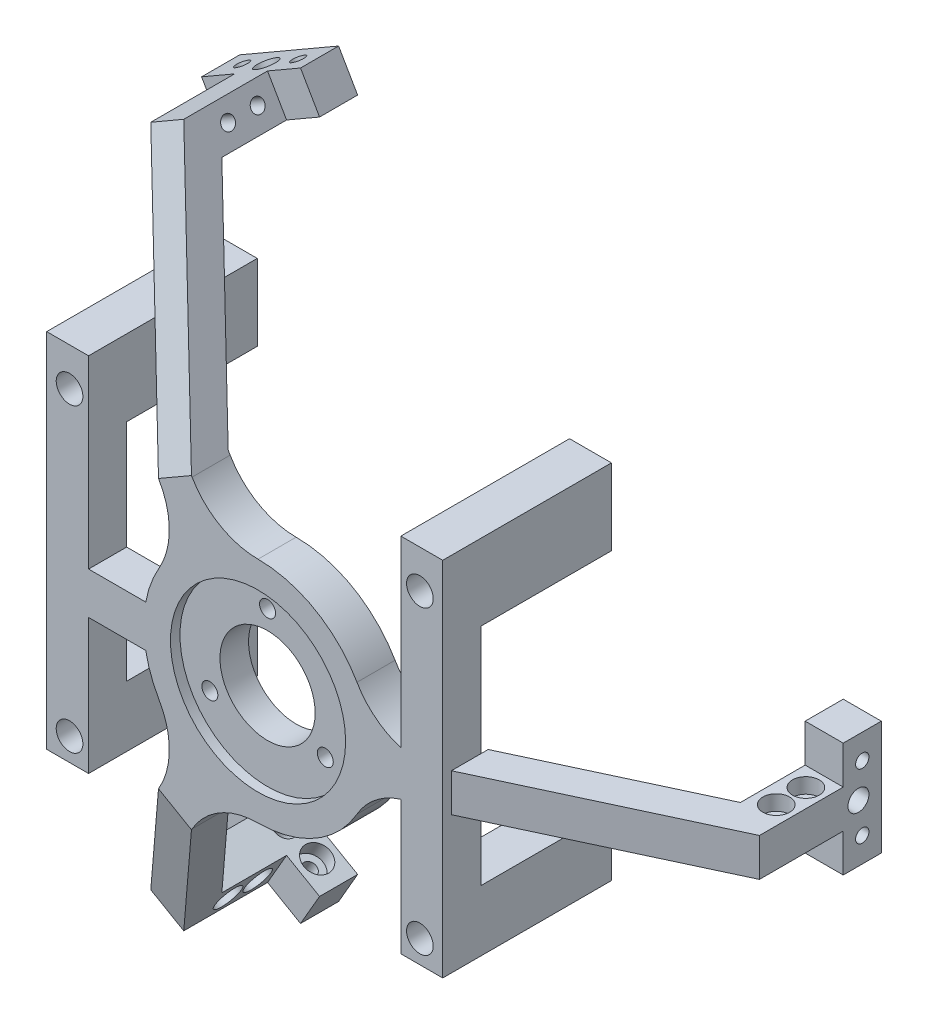
SolidWorks part; units mm, degrees
ref_plane "Plan de face" through (0, 0, 0) normal (0, 0, 1) x (1, 0, 0)
ref_plane "Plan de dessus" through (0, 0, 0) normal (0, 1, 0) x (1, 0, 0)
ref_plane "Plan de droite" through (0, 0, 0) normal (1, 0, 0) x (0, 0, -1)
sketch "Esquisse1" plane through (0, 0, 0) normal (0, 0, 1) x (1, 0, 0)
  line L0 (0, 0) -> (93.67, 0) construction
  line L1 (93.67, 15) -> (103.67, 15)
  line L2 (93.67, 15) -> (93.67, -15)
  line L3 (93.67, -15) -> (103.67, -15)
  line L4 (103.67, 15) -> (103.67, -15)
  line L5 (-33.8446, -88.6206) -> (-59.8254, -73.6206)
  line L6 (-33.8446, -88.6206) -> (-38.8446, -97.2809)
  line L7 (-38.8446, -97.2809) -> (-64.8254, -82.2809)
  line L8 (-59.8254, -73.6206) -> (-64.8254, -82.2809)
  line L9 (-59.8254, 73.6206) -> (-33.8446, 88.6206)
  line L10 (-59.8254, 73.6206) -> (-64.8254, 82.2809)
  line L11 (-64.8254, 82.2809) -> (-38.8446, 97.2809)
  line L12 (-33.8446, 88.6206) -> (-38.8446, 97.2809)
  point P17 (0, 0)
  dimension "D1" = 30
  dimension "D2" = 10
  dimension "D3" = 93.67
  dimension "D4" = 3
extrude "Boss.-Extru.1" add sketch "Esquisse1" along normal blind 10
sketch "Esquisse2" plane through (0, 0, 10) normal (0, 0, 1) x (1, 0, 0)
  line L0 (-57.0272, 86.7831) -> (-46.3532, 92.9458)
  line L1 (-38.8446, 97.2809) -> (-64.8254, 82.2809) construction
  line L2 (93.67, 15) -> (93.67, -15) construction
  line L3 (93.67, 5) -> (103.67, 5)
  line L4 (93.67, 5) -> (93.67, -5)
  line L5 (93.67, -5) -> (103.67, -5)
  line L6 (103.67, 5) -> (103.67, -5)
  line L7 (103.67, -15) -> (103.67, 15) construction
  line L8 (-42.5049, -83.6206) -> (-51.1651, -78.6206)
  line L9 (-42.5049, -83.6206) -> (-47.5049, -92.2809)
  line L10 (-47.5049, -92.2809) -> (-56.1651, -87.2809)
  line L11 (-51.1651, -78.6206) -> (-56.1651, -87.2809)
  line L12 (-51.1651, 78.6206) -> (-42.5049, 83.6206)
  line L13 (-51.1651, 78.6206) -> (-56.1651, 87.2809)
  line L14 (-56.1651, 87.2809) -> (-47.5049, 92.2809)
  line L15 (-42.5049, 83.6206) -> (-47.5049, 92.2809)
  point P12 (93.67, 0)
  point P13 (93.67, 0)
  point P24 (0, 0)
  line M6 (-59.8254, 73.6206) -> (-33.8446, 88.6206)
  dimension "D1" = 3
extrude "Boss.-Extru.2" add sketch "Esquisse2" along normal blind 40 contours L15 L0 L13 M6 | L6 L3 L4 L5 | L8 L11 L10 L9
sketch "Esquisse3" plane through (0, 0, 50) normal (0, 0, 1) x (1, 0, 0)
  line L0 (103.67, 5) -> (103.67, -5) construction
  line L1 (-47.5049, -92.2809) -> (-56.1651, -87.2809) construction
  line L2 (-47.5049, 92.2809) -> (-56.1651, 87.2809) construction
  line L3 (103.67, 5) -> (103.67, -5)
  line L4 (-47.5049, -92.2809) -> (-56.1651, -87.2809)
  line L5 (-47.5049, 92.2809) -> (-56.1651, 87.2809)
  line L6 (-56.1651, -87.2809) -> (-19.1203, -23.1174)
  line L7 (-47.5049, -92.2809) -> (-10.4601, -28.1174)
  line L8 (103.67, -5) -> (29.5804, -5)
  line L9 (103.67, 5) -> (29.5804, 5)
  line L10 (-56.1651, 87.2809) -> (-19.1203, 23.1174)
  line L11 (-47.5049, 92.2809) -> (-10.4601, 28.1174)
  line L12 (-51.1651, -78.6206) -> (-56.1651, -87.2809) construction
  line L13 (-42.5049, -83.6206) -> (-47.5049, -92.2809) construction
  line L14 (93.67, -5) -> (103.67, -5) construction
  line L15 (93.67, 5) -> (103.67, 5) construction
  line L16 (-51.1651, 78.6206) -> (-56.1651, 87.2809) construction
  line L17 (-42.5049, 83.6206) -> (-47.5049, 92.2809) construction
  arc A0 (-19.1203, -23.1174) -> (-19.1203, 23.1174) centre (0, 0) cw
  arc A1 (-10.4601, 28.1174) -> (29.5804, 5) centre (0, 0) cw
  arc A2 (29.5804, -5) -> (-10.4601, -28.1174) centre (0, 0) cw
  dimension "D1" = 30
extrude "Boss.-Extru.3" add sketch "Esquisse3" along normal blind 10
chamfer "Chanfrein1" distance 23 angle 65 3 edges at (93.67, 0, 50) (-46.835, -81.1206, 50) (-46.835, 81.1206, 50)
chamfer "Chanfrein2" distance 28 angle 65 3 edges at (-51.835, -89.7809, 60) (-51.835, 89.7809, 60) (103.67, 0, 60)
fillet "Congé1" radius 20 6 edges at (29.5804, -5, 55) (-10.4601, -28.1174, 55) (-19.1203, -23.1174, 55) (-19.1203, 23.1174, 55) (29.5804, 5, 55) (-10.4601, 28.1174, 55)
sketch "Esquisse4" plane through (0, 0, 60) normal (0, 0, 1) x (1, 0, 0)
  circle A0 centre (0, 0) radius 12.5
  dimension "D1" = 25
extrude "Enlèv. mat.-Extru.1" cut sketch "Esquisse4" against normal up to next
sketch "Esquisse5" plane through (0, 0, 60) normal (0, 0, 1) x (1, 0, 0)
  circle A0 centre (0, 0) radius 23
  dimension "D1" = 46
extrude "Enlèv. mat.-Extru.2" cut sketch "Esquisse5" against normal blind 2.5
sketch "Esquisse6" plane through (0, 0, 57.5) normal (0, 0, 1) x (1, 0, 0)
  line L0 (0, 17.5) -> (0, 0) construction
  circle A0 centre (0, 17.5) radius 2.1
  circle A1 centre (15.1554, -8.75) radius 2.1
  circle A2 centre (-15.1554, -8.75) radius 2.1
  point P10 (0, 0)
  dimension "D2" = 4.2
  dimension "D1" = 17.5
  dimension "D3" = 3
extrude "Enlèv. mat.-Extru.3" cut sketch "Esquisse6" against normal up to next
sketch "Esquisse7" plane through (0, 0, 50) normal (0, 0, -1) x (-1, 0, 0)
  line L0 (0, 0) -> (44.5, 0) construction
  line L1 (-37.5, -41) -> (-48.5, -41)
  line L2 (-37.5, -41) -> (-37.5, 54)
  line L3 (-37.5, 54) -> (-48.5, 54)
  line L4 (-48.5, -41) -> (-48.5, 54)
  line L5 (55.5, -41) -> (44.5, -41)
  line L6 (44.5, -41) -> (44.5, -5.5)
  line L7 (44.5, -5.5) -> (29.4915, -5.5)
  line L8 (55.5, -41) -> (55.5, 54)
  line L9 (55.5, 54) -> (44.5, 54)
  line L10 (44.5, 54) -> (44.5, 5.5)
  line L11 (44.5, 5.5) -> (29.4915, 5.5)
  line L12 (44.5, -5.5) -> (44.5, 5.5) construction
  arc A0 (25.9808, -15) -> (25.9808, 15) centre (0, 0) ccw construction
  arc A1 (29.4915, -5.5) -> (29.4915, 5.5) centre (0, 0) ccw
  point P7 (-43, 54)
  point P22 (44.5, 0)
  point P28 (50, 54)
  dimension "D1" = 11
  dimension "D2" = 41
  dimension "D3" = 95
  dimension "D4" = 43
  dimension "D5" = 93
extrude "Boss.-Extru.4" add sketch "Esquisse7" along normal blind 34.3 and the other way up to surface other way up to face at (23, 0, 60)
sketch "Esquisse8" plane through (0, 0, 15.7) normal (0, 0, -1) x (-1, 0, 0)
  line L0 (-48.5, 6.5) -> (55.5, 6.5) construction
  line L1 (-48.5, 54) -> (-48.5, -41) construction
  line L2 (55.5, -41) -> (55.5, 54) construction
  line L3 (49.5, 44) -> (-42.5, 44) construction
  line L4 (3.5, 6.5) -> (3.5, 44) construction
  line L5 (-48.5, -41) -> (-37.5, -41) construction
  circle A0 centre (49.5, 44) radius 1.75
  circle A1 centre (-42.5, 44) radius 1.75
  circle A2 centre (-42.5, -35) radius 1.75
  circle A3 centre (49.5, -35) radius 1.75
  dimension "D4" = 3.5
  dimension "D1" = 92
  dimension "D2" = 79
  dimension "D3" = 6
extrude "Enlèv. mat.-Extru.4" cut sketch "Esquisse8" against normal up to next
sketch "Esquisse9" plane through (0, 0, 60) normal (0, 0, 1) x (1, 0, 0)
  circle A0 centre (42.5, -35) radius 3.5
  circle A1 centre (42.5, 44) radius 3.5
  circle A2 centre (-49.5, -35) radius 3.5
  circle A3 centre (-49.5, 44) radius 3.5
  dimension "D1" = 7
extrude "Enlèv. mat.-Extru.5" cut sketch "Esquisse9" against normal offset from surface (23.3 mm away) 21 up to face at (40.75, -35, 15.7)
sketch "Esquisse10" plane through (0, 0, 15.7) normal (0, 0, -1) x (-1, 0, 0)
  line L0 (-48.5, 54) -> (-48.5, -41) construction
  line L1 (-48.5, 34) -> (55.5, 34)
  line L2 (-48.5, 34) -> (-48.5, -25)
  line L3 (-48.5, -25) -> (55.5, -25)
  line L4 (55.5, 34) -> (55.5, -25)
  line L5 (55.5, -41) -> (55.5, 54) construction
  circle A0 centre (49.5, 44) radius 1.75 construction
  circle A1 centre (49.5, -35) radius 1.75 construction
  dimension "D1" = 10
  dimension "D2" = 10
extrude "Enlèv. mat.-Extru.6" cut sketch "Esquisse10" against normal up to surface (34.3 mm away) up to face at (-8.6465, 0, 50)
sketch "Esquisse11" plane through (4.3301, -2.5, 0) normal (0.866, -0.5, 0) x (0, 0, -1)
  line L0 (-27, -93.67) -> (-10, -93.67) construction
  line L1 (-10, -93.67) -> (-10, -103.67) construction
  circle A0 centre (-15, -98.86) radius 1.75
  circle A1 centre (-22.78, -98.86) radius 1.75
  dimension "D4" = 3.5
  dimension "D1" = 5.19
  dimension "D2" = 5
  dimension "D3" = 7.78
extrude "Enlèv. mat.-Extru.7" cut sketch "Esquisse11" against normal up to next
sketch "Esquisse12" plane through (4.3301, -2.5, 0) normal (0.866, -0.5, 0) x (0, 0, -1)
  circle A0 centre (-15, -98.86) radius 3.5
  circle A1 centre (-22.78, -98.86) radius 3.5
  dimension "D1" = 7
extrude "Enlèv. mat.-Extru.8" cut sketch "Esquisse12" against normal blind 4
sketch "Esquisse13" plane through (-46.835, -81.1206, 0) normal (0.5, 0.866, 0) x (0.866, -0.5, 0)
  line L0 (-15, -10) -> (-15, 0) construction
  line L1 (-15, -5) -> (-8.5, -5) construction
  line L2 (15, -5) -> (8.5, -5) construction
  line L3 (15, -10) -> (15, 0) construction
  circle A0 centre (-8.5, -5) radius 1.75
  circle A1 centre (8.5, -5) radius 1.75
  dimension "D2" = 3.5
  dimension "D1" = 6.5
extrude "Enlèv. mat.-Extru.9" cut sketch "Esquisse13" against normal up to next
sketch "Esquisse14" plane through (-46.835, -81.1206, 0) normal (0.5, 0.866, 0) x (0.866, -0.5, 0)
  circle A0 centre (-8.5, -5) radius 3.5
  circle A1 centre (8.5, -5) radius 3.5
  dimension "D1" = 7
extrude "Enlèv. mat.-Extru.10" cut sketch "Esquisse14" against normal blind 4
sketch "Esquisse15" plane through (-46.835, -81.1206, 0) normal (0.5, 0.866, 0) x (0.866, -0.5, 0)
  line L0 (15, 0) -> (-15, 0) construction
  line L1 (-15, -10) -> (-15, 0) construction
  circle A0 centre (0, -6) radius 2.75
  point P5 (0, 0)
  point P8 (-15, -5)
  dimension "D1" = 5.5
  dimension "D2" = 1
extrude "Enlèv. mat.-Extru.11" cut sketch "Esquisse15" against normal up to next
pattern_circular "Répétition circulaire1" count 3 over 360 about axis through (0, 0, 0) along (0, 0, 1) of "Enlèv. mat.-Extru.7", "Enlèv. mat.-Extru.11", "Enlèv. mat.-Extru.10", "Enlèv. mat.-Extru.9", "Enlèv. mat.-Extru.8"
